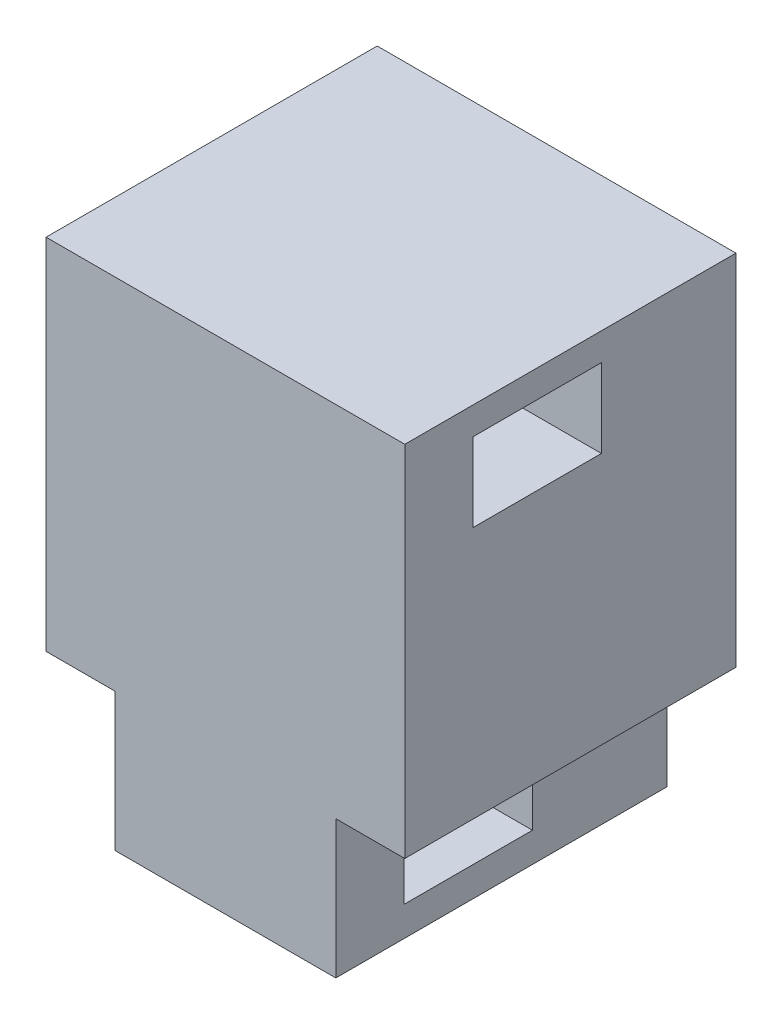
SolidWorks part; units mm, degrees
ref_plane "Front Plane" through (0, 0, 0) normal (0, 0, 1) x (1, 0, 0)
ref_plane "Top Plane" through (0, 0, 0) normal (0, 1, 0) x (1, 0, 0)
ref_plane "Right Plane" through (0, 0, 0) normal (1, 0, 0) x (0, 0, -1)
sketch "Sketch3" plane through (0, 0, 0) normal (0, 0, 1) x (1, 0, 0)
  line L1 (-65, -65) -> (65, -65)
  line L2 (-65, -65) -> (-65, 65)
  line L3 (-65, 65) -> (65, 65)
  line L4 (65, -65) -> (65, 65)
  line L5 (-65, -65) -> (65, 65) construction
  line L6 (-65, 65) -> (65, -65) construction
  point P0 (0, 0)
  dimension "D1" = 130
  dimension "D2" = 130
extrude "Boss-Extrude1" add sketch "Sketch3" against normal blind 120
sketch "Sketch4" plane through (0, 0, 0) normal (0, 0, 1) x (1, 0, 0)
  line L0 (0, -65) -> (0, -118.7219)
  line L1 (-65, -65) -> (65, -65)
  line L5 (0, 0) -> (0, -115)
  line L6 (0, -65) -> (-40, -65)
  line L7 (0, -65) -> (0, -115)
  line L8 (40, -115) -> (-40, -115)
  line L9 (-40, -65) -> (-40, -115)
  line L10 (40, -65) -> (40, -115)
  line M7 (-65, -65) -> (65, -65)
  dimension "D1" = 40
  dimension "D2" = 50
extrude "Boss-Extrude2" add sketch "Sketch4" against normal blind 120 contours L1 L9 L8 L0 | L10 L0 L8 M7
sketch "Sketch6" plane through (40, 0, 0) normal (1, 0, 0) x (0, 0, -1)
  line L0 (0, -65) -> (0, -115) construction
  line L1 (24.75, -75.75) -> (69.25, -75.75)
  line L2 (24.75, -75.75) -> (24.75, -104.25)
  line L11 (71.25, -75.75) -> (69.25, -75.75)
  line L13 (71.25, -75.75) -> (24.75, -75.75)
  line L14 (71.25, -75.75) -> (71.25, -104.25)
  line L15 (71.25, -104.25) -> (24.75, -104.25)
  line L16 (24.75, -75.75) -> (24.75, -104.25)
  line L17 (120, -65) -> (0, -65) construction
  line L18 (120, -65) -> (120, -115) construction
  circle A1 centre (60, -90) radius 10.25
  dimension "D3" = 11.25
  dimension "D4" = 48.75
  dimension "D5" = 14.25
  dimension "D6" = 20.5
  dimension "D1" = 24.75
  dimension "D2" = 10.75
extrude "Cut-Extrude3" cut sketch "Sketch6" against normal blind 34 contours L15 L14 L11 L1 L2 A1 | A1
ref_plane "Plane1" through (0, 0, 0) normal (1, 0, 0) x (0, 0, -1)
mirror "Mirror1" about plane through (0, 0, 0) normal (1, 0, 0) of "Cut-Extrude3"
sketch "Sketch7" plane through (65, 0, 0) normal (1, 0, 0) x (0, 0, -1)
  line L11 (120, 65) -> (0, 65) construction
  line L12 (60, -90) -> (60, 65)
  line L13 (60, 55) -> (60, 26.5)
  line L15 (24.75, 55) -> (71.25, 55)
  line L16 (24.75, 55) -> (24.75, 26.5)
  line L17 (24.75, 26.5) -> (71.25, 26.5)
  line L18 (71.25, 55) -> (71.25, 26.5)
  circle A0 centre (60, 40.75) radius 10.5
  dimension "D5" = 10
  dimension "D2" = 14.25
  dimension "D1" = 11.25
  dimension "D3" = 14.25
  dimension "D4" = 46.5
extrude "Cut-Extrude5" cut sketch "Sketch7" against normal blind 34 contours A0 L12 L15 L16 L17 | A0 L12 L17 L18 L15 | L13 A0 | L13 A0
ref_plane "Plane3" through (0, 0, 0) normal (1, 0, 0) x (0, 0, -1)
mirror "Mirror3" about plane through (0, 0, 0) normal (1, 0, 0) of "Cut-Extrude5"
sketch "Sketch8" plane through (-3, 0, 0) normal (1, 0, 0) x (0, 0, -1)
  line L1 (24.75, 55) -> (71.25, 55)
  line L2 (24.75, 55) -> (24.75, 26.5)
  line L3 (24.75, 26.5) -> (71.25, 26.5)
  line L4 (71.25, 55) -> (71.25, 26.5)
extrude "Boss-Extrude3" add sketch "Sketch8" along normal blind 34
